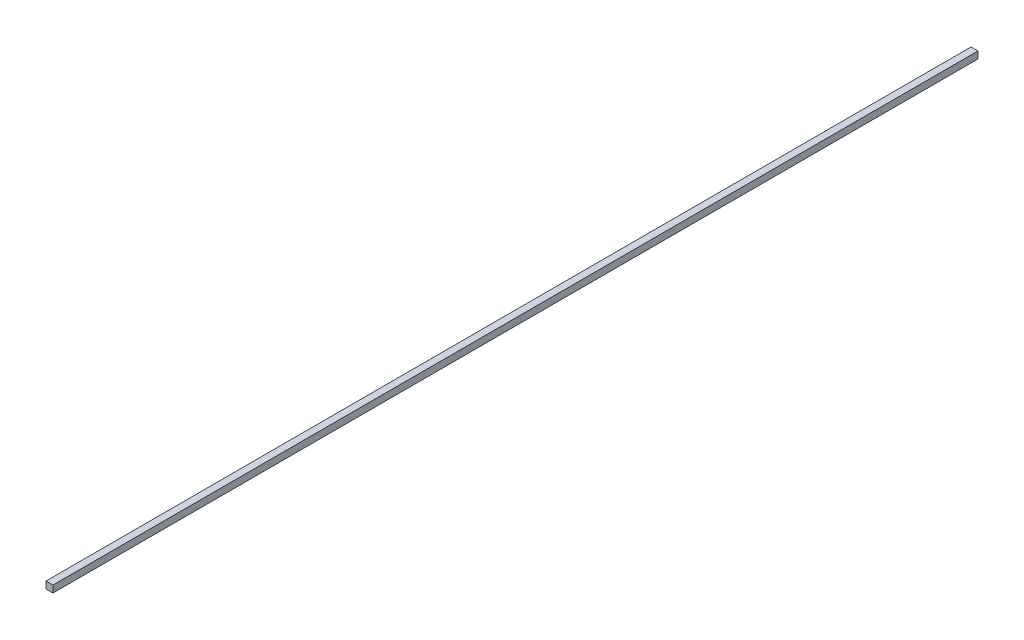
SolidWorks part; units mm, degrees
ref_plane "Front Plane" through (0, 0, 0) normal (0, 0, 1) x (1, 0, 0)
ref_plane "Top Plane" through (0, 0, 0) normal (0, 1, 0) x (1, 0, 0)
ref_plane "Right Plane" through (0, 0, 0) normal (1, 0, 0) x (0, 0, -1)
sketch "Sketch1" plane through (0, 0, 0) normal (0, 0, 1) x (1, 0, 0)
  line L1 (-7.5, 7.5) -> (7.5, 7.5)
  line L2 (-7.5, 7.5) -> (-7.5, -7.5)
  line L3 (-7.5, -7.5) -> (7.5, -7.5)
  line L4 (7.5, 7.5) -> (7.5, -7.5)
  line L5 (-7.5, 7.5) -> (7.5, -7.5) construction
  line L6 (-7.5, -7.5) -> (7.5, 7.5) construction
  point P0 (0, 0)
  dimension "D1" = 15
  dimension "D2" = 15
extrude "Boss-Extrude1" add sketch "Sketch1" along normal blind 2000
